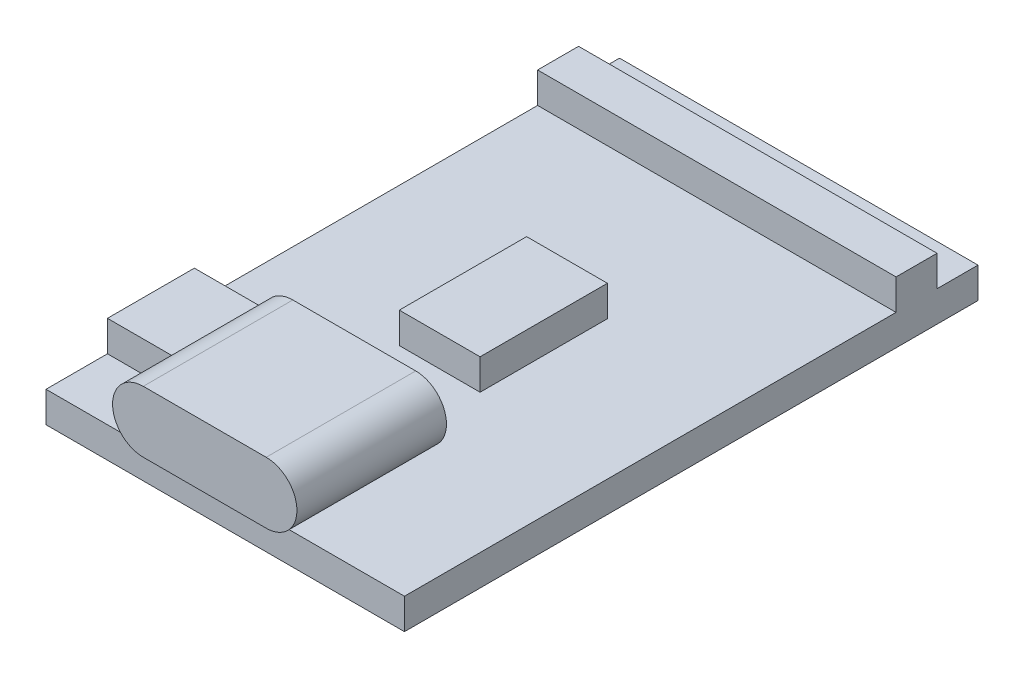
SolidWorks part; units mm, degrees
ref_plane "Спереди" through (0, 0, 0) normal (0, 0, 1) x (1, 0, 0)
ref_plane "Сверху" through (0, 0, 0) normal (0, 1, 0) x (1, 0, 0)
ref_plane "Справа" through (0, 0, 0) normal (1, 0, 0) x (0, 0, -1)
sketch "Эскиз1" plane through (0, 0, 0) normal (0, 1, 0) x (1, 0, 0)
  line L1 (-8.75, 0) -> (8.75, 0)
  line L2 (-8.75, 0) -> (-8.75, 28)
  line L3 (-8.75, 28) -> (8.75, 28)
  line L4 (8.75, 0) -> (8.75, 28)
  point P4 (0, 0)
  point P6 (0, -3)
  dimension "D1" = 28
  dimension "D2" = 17.5
  dimension "D3" = 3
extrude "Бобышка-Вытянуть1" add sketch "Эскиз1" along normal blind 1.5
sketch "Эскиз2" plane through (0, 0, 0) normal (0, 0, 1) x (1, 0, 0)
  line L0 (-3, 3.5) -> (3, 3.5) construction
  line L1 (-3, 5) -> (3, 5)
  line L2 (-3, 2) -> (3, 2)
  line L3 (0, 3.5) -> (0, 0) construction
  line L4 (-8.75, 0) -> (8.75, 0) construction
  arc A0 (-3, 5) -> (-3, 2) centre (-3, 3.5) ccw
  arc A1 (3, 2) -> (3, 5) centre (3, 3.5) ccw
  point P2 (0, 3.5)
  point P11 (-4.5, 3.5)
  point P12 (4.5, 3.5)
  dimension "D1" = 5
  dimension "D2" = 3
  dimension "D3" = 9
extrude "Бобышка-Вытянуть2" add sketch "Эскиз2" against normal blind 7.3 from offset 1 separate body
ref_plane "Плоскость4" through (0, 0, 3) normal (0, 0, 1) x (1, 0, 0)
sketch "Эскиз3" plane through (0, 0, 0) normal (0, 1, 0) x (1, 0, 0)
  line L0 (0, 10.4702) -> (0, 0) construction
  line L1 (-1.9721, 10.4702) -> (1.9721, 10.4702)
  line L2 (-1.9721, 10.4702) -> (-1.9721, 16.6852)
  line L3 (-1.9721, 16.6852) -> (1.9721, 16.6852)
  line L4 (1.9721, 10.4702) -> (1.9721, 16.6852)
  line L5 (-8.75, 28) -> (-8.75, 0) construction
  line L6 (-8.75, 3) -> (-5.2987, 3)
  line L7 (-8.75, 3) -> (-8.75, 7.2431)
  line L8 (-8.75, 7.2431) -> (-5.2987, 7.2431)
  line L9 (-5.2987, 3) -> (-5.2987, 7.2431)
  line L10 (8.75, 0) -> (8.75, 28) construction
  line L11 (-8.75, 26) -> (8.75, 26)
  line L12 (-8.75, 26) -> (-8.75, 24)
  line L13 (-8.75, 24) -> (8.75, 24)
  line L14 (8.75, 26) -> (8.75, 24)
  line L15 (8.75, 28) -> (-8.75, 28) construction
  line L16 (0, 26) -> (0, 28) construction
  line L17 (0, 26) -> (0, 24) construction
  dimension "D1" = 3
  dimension "D2" = 2
extrude "Бобышка-Вытянуть3" add sketch "Эскиз3" along normal blind 3
